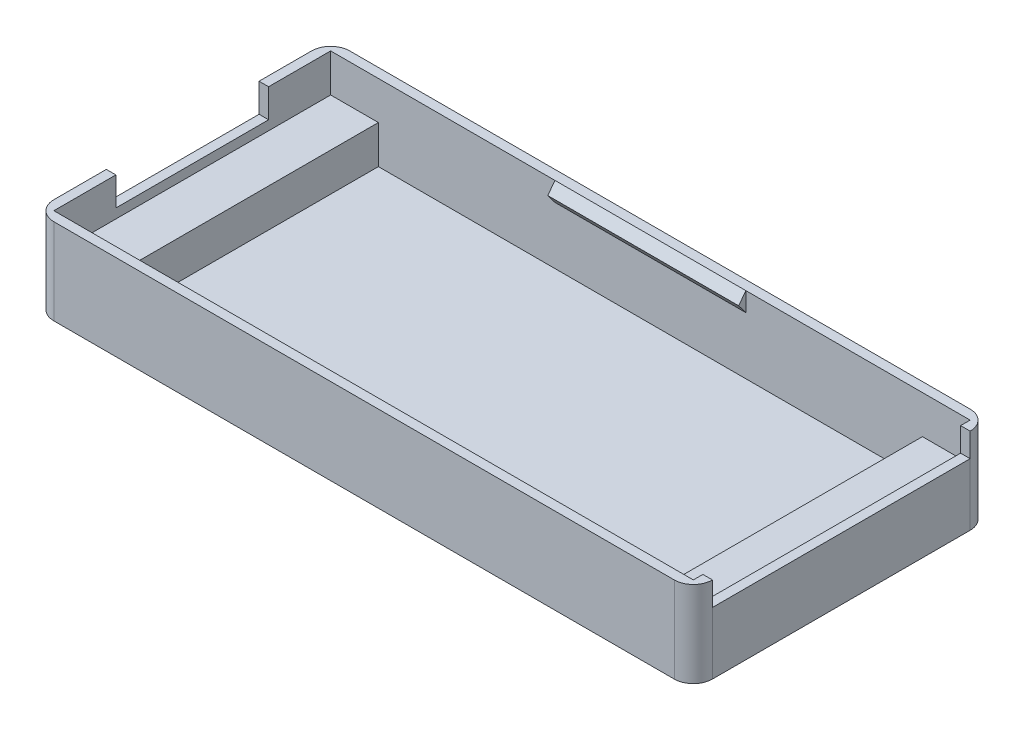
SolidWorks part; units mm, degrees
ref_plane "Front Plane" through (0, 0, 0) normal (0, 0, 1) x (1, 0, 0)
ref_plane "Top Plane" through (0, 0, 0) normal (0, 1, 0) x (1, 0, 0)
ref_plane "Right Plane" through (0, 0, 0) normal (1, 0, 0) x (0, 0, -1)
sketch "Sketch1" plane through (0, 0, 0) normal (0, 1, 0) x (1, 0, 0)
  line L1 (-32.5, -15.5) -> (32.5, -15.5)
  line L2 (-34.5, -13.5) -> (-34.5, 13.5)
  line L3 (-32.5, 15.5) -> (32.5, 15.5)
  line L4 (34.5, -13.5) -> (34.5, 13.5)
  line L5 (-34.5, -15.5) -> (34.5, 15.5) construction
  line L6 (-34.5, 15.5) -> (34.5, -15.5) construction
  arc A0 (-32.5, -15.5) -> (-34.5, -13.5) centre (-32.5, -13.5) cw
  arc A1 (32.5, -15.5) -> (34.5, -13.5) centre (32.5, -13.5) ccw
  arc A2 (32.5, 15.5) -> (34.5, 13.5) centre (32.5, 13.5) cw
  arc A3 (-34.5, 13.5) -> (-32.5, 15.5) centre (-32.5, 13.5) cw
  point P0 (0, 0)
  dimension "D1" = 2
  dimension "D2" = 69
  dimension "D3" = 31
extrude "Boss-Extrude1" add sketch "Sketch1" along normal blind 9
sketch "Sketch4" plane through (0, 9, 0) normal (0, 1, 0) x (1, 0, 0)
  line L1 (-33.5, -14.5) -> (33.5, -14.5)
  line L2 (-33.5, -14.5) -> (-33.5, 14.5)
  line L3 (-33.5, 14.5) -> (33.5, 14.5)
  line L4 (33.5, -14.5) -> (33.5, 14.5)
  line L5 (-33.5, -14.5) -> (33.5, 14.5) construction
  line L6 (-33.5, 14.5) -> (33.5, -14.5) construction
  point P0 (0, 0)
  dimension "D1" = 67
  dimension "D2" = 29
extrude "Cut-Extrude1" cut sketch "Sketch4" against normal blind 4
sketch "Sketch7" plane through (33.5, 0, 0) normal (-1, 0, 0) x (0, 0, 1)
  line L1 (-13.5, 9) -> (13.5, 9)
  line L2 (-13.5, 9) -> (-13.5, 6.5)
  line L3 (-13.5, 6.5) -> (13.5, 6.5)
  line L4 (13.5, 9) -> (13.5, 6.5)
  line L6 (14.5, 5) -> (-14.5, 5) construction
  dimension "D1" = 1.5
extrude "Cut-Extrude2" cut sketch "Sketch7" against normal blind 19
sketch "Sketch9" plane through (0, 5, 0) normal (0, 1, 0) x (1, 0, 0)
  line L0 (33.5, 13.5) -> (33.5, -13.5) construction
  line L1 (-28.5, 14.5) -> (28.5, 14.5)
  line L2 (-28.5, 14.5) -> (-28.5, -14.5)
  line L3 (-28.5, -14.5) -> (28.5, -14.5)
  line L4 (28.5, 14.5) -> (28.5, -14.5)
  line L5 (-33.5, 14.5) -> (-33.5, -14.5) construction
  line L6 (33.5, 14.5) -> (-33.5, 14.5) construction
  line L7 (-33.5, -14.5) -> (33.5, -14.5) construction
  dimension "D1" = 5
  dimension "D2" = 5
extrude "Cut-Extrude3" cut sketch "Sketch9" against normal blind 4
sketch "Sketch10" plane through (-33.5, 0, 0) normal (1, 0, 0) x (0, 0, -1)
  line L0 (14.5, 9) -> (-14.5, 9) construction
  line L1 (-8, 9) -> (8, 9)
  line L2 (-8, 9) -> (-8, 6)
  line L3 (-8, 6) -> (8, 6)
  line L4 (8, 9) -> (8, 6)
  line L5 (14.5, 5) -> (-14.5, 5) construction
  point P6 (0, 9)
  dimension "D1" = 16
  dimension "D2" = 1
extrude "Cut-Extrude4" cut sketch "Sketch10" against normal blind 4
sketch "Sketch13" plane through (0, 0, 0) normal (1, 0, 0) x (0, 0, -1)
  line L3 (14.5, 7) -> (14.5, 9)
  line L4 (14.5, 9) -> (13.75, 8)
  line L5 (13.75, 8) -> (14.5, 7)
  line L9 (0, 0) -> (0, 16.06) construction
  line L10 (-13.75, 8) -> (-14.5, 7)
  line L11 (-14.5, 9) -> (-13.75, 8)
  line L12 (-14.5, 7) -> (-14.5, 9)
  dimension "D3" = 0.75
  dimension "D4" = 1
extrude "Boss-Extrude4" add sketch "Sketch13" along normal mid plane 20
